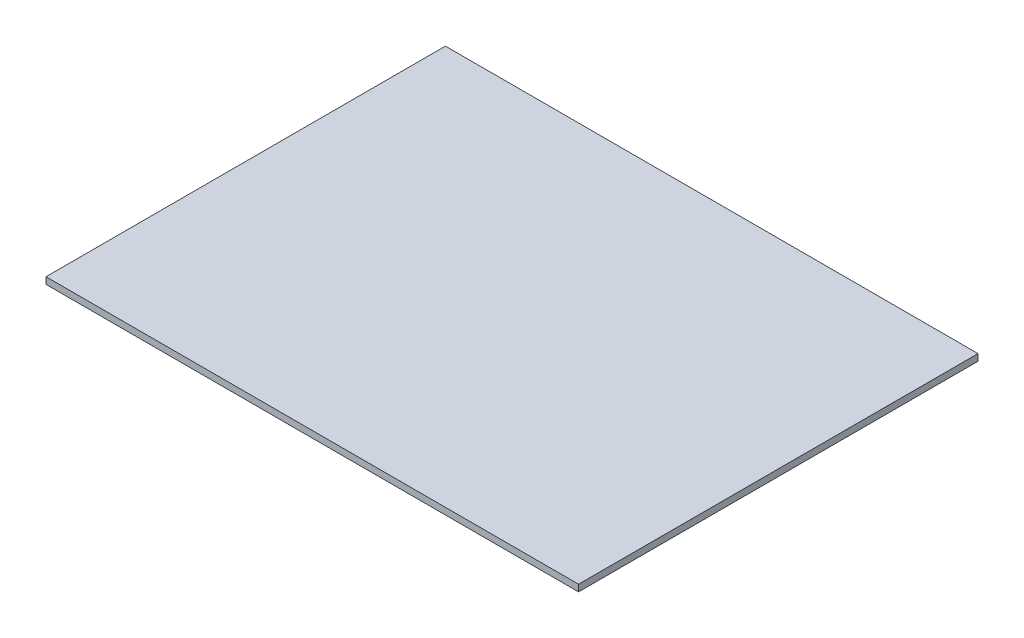
SolidWorks part; units mm, degrees
ref_plane "Front Plane" through (0, 0, 0) normal (0, 0, 1) x (1, 0, 0)
ref_plane "Top Plane" through (0, 0, 0) normal (0, 1, 0) x (1, 0, 0)
ref_plane "Right Plane" through (0, 0, 0) normal (1, 0, 0) x (0, 0, -1)
sketch "Sketch1" plane through (0, 0, 0) normal (0, 1, 0) x (1, 0, 0)
  line L1 (-127, 95.25) -> (127, 95.25)
  line L2 (-127, 95.25) -> (-127, -95.25)
  line L3 (-127, -95.25) -> (127, -95.25)
  line L4 (127, 95.25) -> (127, -95.25)
  line L5 (-127, 95.25) -> (127, -95.25) construction
  line L6 (-127, -95.25) -> (127, 95.25) construction
  point P0 (0, 0)
  dimension "D1" = 190.5
  dimension "D2" = 254
extrude "Boss-Extrude1" add sketch "Sketch1" along normal blind 3.175
